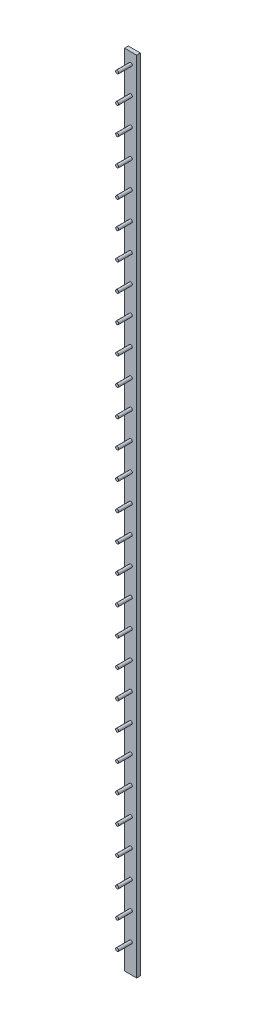
SolidWorks part; units mm, degrees
ref_plane "Front Plane" through (0, 0, 0) normal (0, 0, 1) x (1, 0, 0)
ref_plane "Top Plane" through (0, 0, 0) normal (0, 1, 0) x (1, 0, 0)
ref_plane "Right Plane" through (0, 0, 0) normal (1, 0, 0) x (0, 0, -1)
sketch "Sketch2" plane through (0, 0, 0) normal (0, 0, 1) x (1, 0, 0)
  line L1 (-10.16, 673.1) -> (10.16, 673.1)
  line L2 (-10.16, 673.1) -> (-10.16, -673.1)
  line L3 (-10.16, -673.1) -> (10.16, -673.1)
  line L4 (10.16, 673.1) -> (10.16, -673.1)
  line L5 (-10.16, 673.1) -> (10.16, -673.1) construction
  line L6 (-10.16, -673.1) -> (10.16, 673.1) construction
  point P0 (0, 0)
  dimension "D1" = 20.32
  dimension "D2" = 1346.2
extrude "Boss-Extrude1" add sketch "Sketch2" along normal blind 6.35
sketch "Sketch3" plane through (0, 0, 6.35) normal (0, 0, 1) x (1, 0, 0)
  circle A0 centre (0.2673, 654.8534) radius 2.6164
  circle A1 centre (0.2673, 609.1334) radius 2.6164
  circle A2 centre (0.2673, 563.4134) radius 2.6164
  circle A3 centre (0.2673, 517.6934) radius 2.6164
  circle A4 centre (0.2673, 471.9734) radius 2.6164
  circle A5 centre (0.2673, 426.2534) radius 2.6164
  circle A6 centre (0.2673, 380.5334) radius 2.6164
  circle A7 centre (0.2673, 334.8134) radius 2.6164
  circle A8 centre (0.2673, 289.0934) radius 2.6164
  circle A9 centre (0.2673, 243.3734) radius 2.6164
  circle A10 centre (0.2673, 197.6534) radius 2.6164
  circle A11 centre (0.2673, 151.9334) radius 2.6164
  circle A12 centre (0.2673, 106.2134) radius 2.6164
  circle A13 centre (0.2673, 60.4934) radius 2.6164
  circle A14 centre (0.2673, 14.7734) radius 2.6164
  circle A15 centre (0.2673, -30.9466) radius 2.6164
  circle A16 centre (0.2673, -76.6666) radius 2.6164
  circle A17 centre (0.2673, -122.3866) radius 2.6164
  circle A18 centre (0.2673, -168.1066) radius 2.6164
  circle A19 centre (0.2673, -213.8266) radius 2.6164
  circle A20 centre (0.2673, -259.5466) radius 2.6164
  circle A21 centre (0.2673, -305.2666) radius 2.6164
  circle A22 centre (0.2673, -350.9866) radius 2.6164
  circle A23 centre (0.2673, -396.7066) radius 2.6164
  circle A24 centre (0.2673, -442.4266) radius 2.6164
  circle A25 centre (0.2673, -488.1466) radius 2.6164
  circle A26 centre (0.2673, -533.8666) radius 2.6164
  circle A27 centre (0.2673, -579.5866) radius 2.6164
  circle A28 centre (0.2673, -625.3066) radius 2.6164
  circle A30 centre (0.2673, -671.0266) radius 2.6164 [skipped]
  point P50 (0.6162, 654.9157)
  point P51 (0.2673, 654.8534)
  dimension "D3" = 30
  dimension "D1" = 45.72
extrude "Boss-Extrude2" add sketch "Sketch3" along normal blind 22.86
